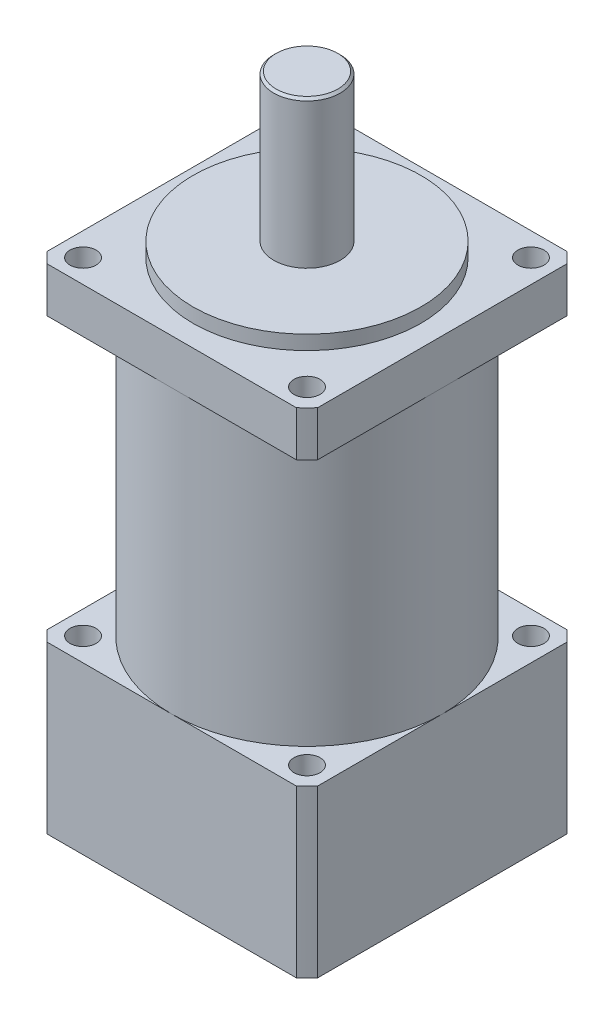
SolidWorks part; units mm, degrees
ref_plane "前视基准面" through (0, 0, 0) normal (0, 0, 1) x (1, 0, 0)
ref_plane "上视基准面" through (0, 0, 0) normal (0, 1, 0) x (1, 0, 0)
ref_plane "右视基准面" through (0, 0, 0) normal (1, 0, 0) x (0, 0, -1)
sketch "草图1" plane through (0, 0, 0) normal (0, 1, 0) x (1, 0, 0)
  line L1 (-28.5, 28.5) -> (28.5, 28.5)
  line L2 (-28.5, 28.5) -> (-28.5, -28.5)
  line L3 (-28.5, -28.5) -> (28.5, -28.5)
  line L4 (28.5, 28.5) -> (28.5, -28.5)
  line L5 (-28.5, 28.5) -> (28.5, -28.5) construction
  line L6 (-28.5, -28.5) -> (28.5, 28.5) construction
  circle A0 centre (0, 0) radius 38.75
  dimension "D1" = 77.5
  dimension "D2" = 57
extrude "凸台-拉伸1" add sketch "草图1" along normal blind 35 contours L3 A0 L4 L1 L2
sketch "草图2" plane through (0, 35, 0) normal (0, 1, 0) x (1, 0, 0)
  circle A0 centre (0, 0) radius 28.5
  dimension "D1" = 57
extrude "凸台-拉伸2" add sketch "草图2" along normal blind 69
sketch "草图3" plane through (0, 104, 0) normal (0, 1, 0) x (1, 0, 0)
  line L4 (-26.2548, -28.5) -> (26.2548, -28.5)
  line L5 (-28.5, 26.2548) -> (-28.5, -26.2548)
  line L6 (26.2548, 28.5) -> (-26.2548, 28.5)
  line L7 (28.5, -26.2548) -> (28.5, 26.2548)
  line L8 (-26.2548, -28.5) -> (26.2548, -28.5)
  line L9 (-28.5, 26.2548) -> (-28.5, -26.2548)
  line L10 (26.2548, 28.5) -> (-26.2548, 28.5)
  line L11 (28.5, -26.2548) -> (28.5, 26.2548)
  arc A4 (-28.5, -26.2548) -> (-26.2548, -28.5) centre (0, 0) ccw
  arc A5 (-26.2548, 28.5) -> (-28.5, 26.2548) centre (0, 0) ccw
  arc A6 (28.5, 26.2548) -> (26.2548, 28.5) centre (0, 0) ccw
  arc A7 (26.2548, -28.5) -> (28.5, -26.2548) centre (0, 0) ccw
  arc A8 (-28.5, -26.2548) -> (-26.2548, -28.5) centre (0, 0) ccw
  arc A9 (-26.2548, 28.5) -> (-28.5, 26.2548) centre (0, 0) ccw
  arc A10 (28.5, 26.2548) -> (26.2548, 28.5) centre (0, 0) ccw
  arc A11 (26.2548, -28.5) -> (28.5, -26.2548) centre (0, 0) ccw
  dimension "D1" = 0
extrude "凸台-拉伸3" add sketch "草图3" against normal blind 9.5
sketch "草图4" plane through (0, 104, 0) normal (0, 1, 0) x (1, 0, 0)
  circle A0 centre (0, 0) radius 24
  dimension "D1" = 48
extrude "凸台-拉伸4" add sketch "草图4" along normal blind 3
sketch "草图5" plane through (0, 107, 0) normal (0, 1, 0) x (1, 0, 0)
  circle A0 centre (0, 0) radius 7
  dimension "D1" = 14
extrude "凸台-拉伸5" add sketch "草图5" along normal blind 31
sketch "草图6" plane through (0, 0, 0) normal (0, -1, 0) x (1, 0, 0)
  line L1 (23.582, -23.582) -> (-23.582, -23.582) construction
  line L2 (23.582, -23.582) -> (23.582, 23.582) construction
  line L3 (23.582, 23.582) -> (-23.582, 23.582) construction
  line L4 (-23.582, -23.582) -> (-23.582, 23.582) construction
  line L5 (23.582, -23.582) -> (-23.582, 23.582) construction
  line L6 (23.582, 23.582) -> (-23.582, -23.582) construction
  circle A0 centre (0, 0) radius 33.35 construction
  circle A1 centre (-23.582, 23.582) radius 2.75
  circle A2 centre (23.582, 23.582) radius 2.75
  circle A3 centre (23.582, -23.582) radius 2.75
  circle A4 centre (-23.582, -23.582) radius 2.75
  point P17 (0, 0)
  dimension "D1" = 66.7
  dimension "D2" = 5.5
  dimension "D3" = 4
extrude "切除-拉伸1" cut sketch "草图6" against normal blind 297
sketch "草图7" plane through (0, 0, 0) normal (0, -1, 0) x (1, 0, 0)
  circle A0 centre (0, 0) radius 21
  dimension "D1" = 42
extrude "切除-拉伸2" cut sketch "草图7" against normal blind 22
sketch "草图8" plane through (0, 22, 0) normal (0, -1, 0) x (1, 0, 0)
  line L0 (0, 4) -> (0, 19.05) construction
  line L1 (-0.8, 19.0332) -> (-0.8, 3.9192)
  line L2 (0.8, 19.0332) -> (0.8, 3.9192)
  circle A0 centre (0, 0) radius 19.05
  circle A1 centre (0, 0) radius 4
  dimension "D1" = 38.1
  dimension "D2" = 8
  dimension "D3" = 1.6
extrude "凸台-拉伸6" add sketch "草图8" along normal offset from surface (17 mm away) 5 contours A1 L1 A0 L2
chamfer "倒角1" distance 0.5 angle 45 1 edges at (0, 138, 7)
